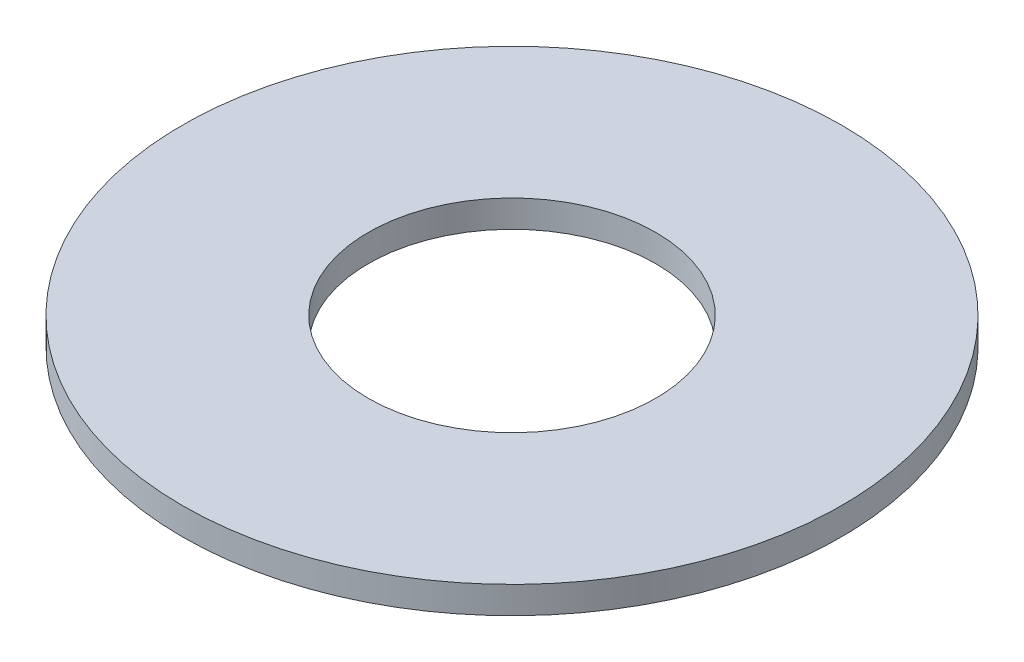
SolidWorks part; units mm, degrees
ref_plane "Front Plane" through (0, 0, 0) normal (0, 0, 1) x (1, 0, 0)
ref_plane "Top Plane" through (0, 0, 0) normal (0, 1, 0) x (1, 0, 0)
ref_plane "Right Plane" through (0, 0, 0) normal (1, 0, 0) x (0, 0, -1)
sketch "Sketch1" plane through (0, 0, 0) normal (0, 1, 0) x (1, 0, 0)
  circle A0 centre (0, 0) radius 36.45
  circle A1 centre (0, 0) radius 15.9
  dimension "D1" = 31.8
  dimension "D2" = 72.9
extrude "Boss-Extrude1" add sketch "Sketch1" along normal blind 3
